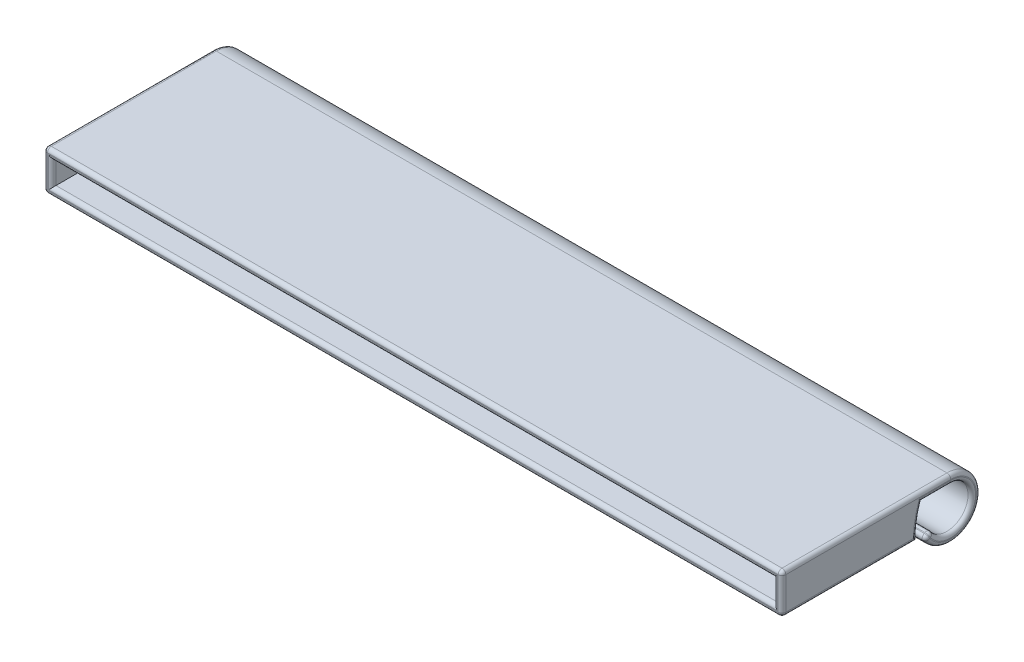
SolidWorks part; units mm, degrees
ref_plane "Front Plane" through (0, 0, 0) normal (0, 0, 1) x (1, 0, 0)
ref_plane "Top Plane" through (0, 0, 0) normal (0, 1, 0) x (1, 0, 0)
ref_plane "Right Plane" through (0, 0, 0) normal (1, 0, 0) x (0, 0, -1)
sketch "Sketch2" plane through (0, 0, 0) normal (1, 0, 0) x (0, 0, -1)
  line L0 (0, 0) -> (4, 0)
  line L1 (0, 0.2) -> (4, 0.2)
  line L2 (0, 0.2) -> (0, 0)
  line L3 (3.5539, -0.7258) -> (3.3754, -0.8161)
  arc A0 (4, 0) -> (3.5539, -0.7258) centre (4, -0.5) cw
  arc A1 (4, 0.2) -> (3.3754, -0.8161) centre (4, -0.5) cw
  dimension "D2" = 0.5
  dimension "D1" = 4
  dimension "D3" = 0.2
extrude "Boss-Extrude1" add sketch "Sketch2" along normal mid plane 17.5
sketch "Sketch3" plane through (8.75, 0, 0) normal (1, 0, 0) x (0, 0, -1)
  line L0 (0, 0) -> (0, -0.7499)
  line L1 (0, -0.7499) -> (3.1997, -0.7499)
  line L2 (0, 0) -> (4, 0) construction
  line L3 (3.3208, 0) -> (0, 0)
  arc A0 (3.1997, -0.7499) -> (3.3208, 0) centre (5.5823, -0.7499) cw
  dimension "D1" = 0.7499
extrude "Boss-Extrude2" add sketch "Sketch3" against normal blind 0.2
mirror "Mirror1" about plane through (0, 0, 0) normal (1, 0, 0) of "Boss-Extrude2"
sketch "Sketch4" plane through (0, 0, 0) normal (1, 0, 0) x (0, 0, -1)
  line L1 (0, -0.7499) -> (3.1737, -0.7499)
  line L2 (0, -0.7499) -> (0, -0.5499)
  line L3 (0, -0.5499) -> (3.1737, -0.5499)
  line L4 (3.1737, -0.7499) -> (3.1737, -0.5499)
  dimension "D1" = 0.2
extrude "Boss-Extrude3" add sketch "Sketch4" along normal up to surface and the other way up to surface up to face at (8.55, -0.3737, -1.6226) other way up to face at (-8.55, -0.3737, -1.6226)
fillet "Fillet1" radius 0.09 24 edges at (0, 0.2, 0) (0, -0.8161, -3.3754) (0, -0.7258, -3.5539) (8.75, -0.7618, -4.426) (8.75, -0.7709, -3.4647) (8.75, 0, -3.6604) (0, 0, 0) (8.75, -0.8666, -4.5963) (8.55, -0.2749, 0) (0, -0.7499, 0) (8.75, -0.7499, -1.5999) (8.75, -0.3701, -3.2302) (8.75, 0.2, -2) (-8.75, 0, -3.6604) (-8.75, -0.7499, -1.5999) (-8.75, -0.3701, -3.2302) (-8.55, -0.2749, 0) (0, -0.5499, 0) (8.75, -0.2749, 0) (-8.75, 0.2, -2) (-8.75, -0.8666, -4.5963) (-8.75, -0.7709, -3.4647) (-8.75, -0.7618, -4.426) (-8.75, -0.2749, 0)
